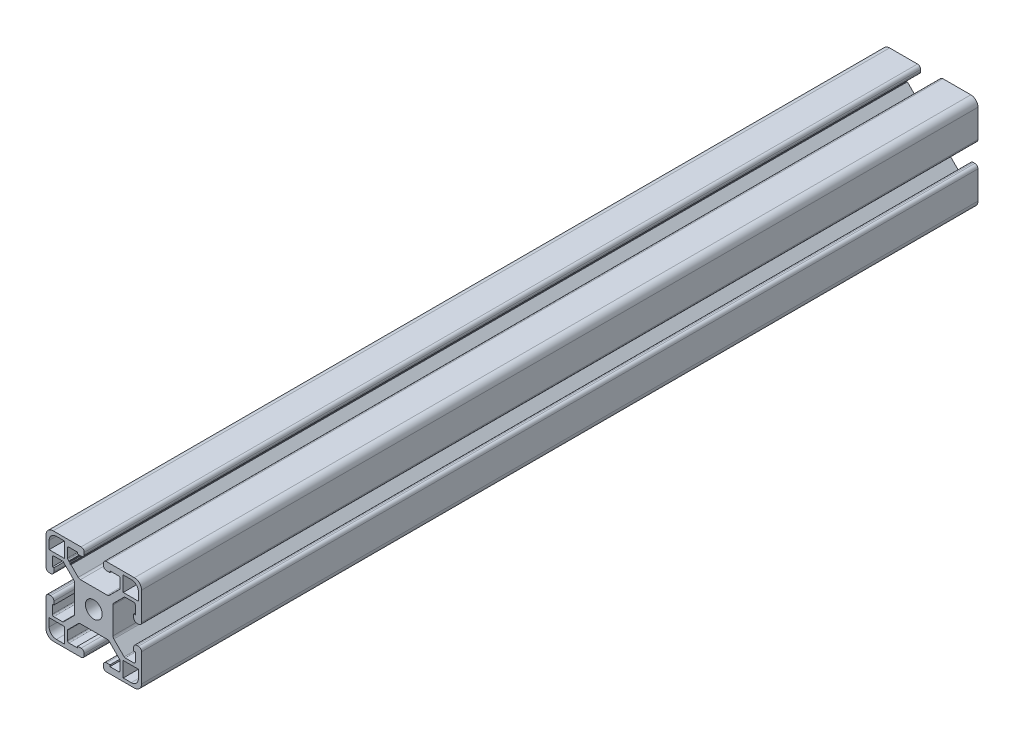
SolidWorks part; units mm, degrees
ref_plane "Front Plane" through (0, 0, 0) normal (0, 0, 1) x (1, 0, 0)
ref_plane "Top Plane" through (0, 0, 0) normal (0, 1, 0) x (1, 0, 0)
ref_plane "Right Plane" through (0, 0, 0) normal (1, 0, 0) x (0, 0, -1)
sketch "Sketch2" plane through (0, 0, 0) normal (0, 0, 1) x (1, 0, 0)
  line L0 (0, 20) -> (0, -20) construction
  line L1 (-20, 0) -> (20, 0) construction
  line L2 (4, -20) -> (20, -20)
  line L3 (20, -20) -> (20, -4)
  line L5 (6.75, -17.36) -> (10.4, -17.36)
  line L7 (0, 0) -> (20, -20) construction
  line L9 (17.36, -6.75) -> (17.36, -10.4)
  line L11 (10.4334, -8.5666) -> (8.5666, -10.4334) construction
  line L12 (11, -16.76) -> (11, -12.8668)
  line L13 (6.1332, -8) -> (11, -12.8668)
  line L14 (16.76, -11) -> (12.8668, -11)
  line L15 (8, -6.1332) -> (12.8668, -11)
  line L16 (4, -20) -> (4, -16.7)
  line L18 (4, -16.7) -> (6.75, -16.7)
  line L19 (6.75, -16.7) -> (6.75, -17.36)
  line L20 (20, -4) -> (16.7, -4)
  line L21 (16.7, -4) -> (16.7, -6.75)
  line L22 (16.7, -6.75) -> (17.36, -6.75)
  line L23 (6.75, -17.36) -> (6.75, -20) construction
  circle A0 centre (0, 0) radius 3.5
  arc A1 (10.4, -17.36) -> (11, -16.76) centre (10.4, -16.76) ccw
  arc A2 (17.36, -10.4) -> (16.76, -11) centre (16.76, -10.4) cw
  point P8 (0, -8)
  point P16 (9.5, -9.5)
  dimension "Center Hole Diameter" = 7
  dimension "D3" = 0.6
  dimension "Rail Height" = 40
  dimension "Rail Width" = 40
  dimension "T-Slot Width" = 8
  dimension "Slot Depth" = 12
  dimension "Inner Slot Width" = 22
  dimension "D1" = 2.75
  dimension "D2" = 3.3
  dimension "D4" = 0.66
sketch "Sketch3" plane through (0, 0, 0) normal (1, 0, 0) x (0, 0, -1)
  line L0 (-175, -20) -> (175, -20) construction
  line L1 (-149.6, 0) -> (149.6, 0) construction
  dimension "Length" = 350
  dimension "D1" = 25.4
sketch "Sketch4" plane through (0, 0, 0) normal (0, 0, 1) x (1, 0, 0)
  line L1 (20, -17) -> (20, -5.32)
  line L2 (20, -4) -> (16.7, -4) construction
  line L3 (16.7, -4) -> (16.7, -6.75) construction
  line L7 (18.02, -4) -> (18.68, -4)
  line L9 (16.7, -5.32) -> (16.7, -6.75)
  line L10 (16.7, -6.75) -> (17.36, -6.75)
  line L11 (17.36, -6.75) -> (17.36, -10.4)
  line L13 (16.76, -11) -> (13.1153, -11)
  line L18 (16.76, -11) -> (12.8668, -11) construction
  line L20 (8, -6.1332) -> (12.8668, -11) construction
  line L22 (4, -20) -> (20, -20) construction
  line L23 (20, -20) -> (20, -4) construction
  line L24 (17, -20) -> (5.32, -20)
  line L25 (4, -18.02) -> (4, -18.68)
  line L26 (4, -20) -> (4, -16.7) construction
  line L27 (4, -16.7) -> (6.75, -16.7) construction
  line L28 (5.32, -16.7) -> (6.75, -16.7)
  line L29 (6.75, -16.7) -> (6.75, -17.36)
  line L30 (6.75, -17.36) -> (10.4, -17.36)
  line L31 (6.1332, -8) -> (11, -12.8668) construction
  line L32 (11, -16.76) -> (11, -12.8668) construction
  line L33 (11, -13.1153) -> (11, -16.76)
  line L34 (0, -8) -> (5.5865, -8)
  line L35 (6.5199, -8.3866) -> (10.8243, -12.691)
  line L36 (12.691, -10.8243) -> (8.3866, -6.5199)
  line L37 (8, 0) -> (8, -5.5865)
  line L38 (-20, 0) -> (20, 0) construction
  line L39 (15.68, -18.68) -> (12.32, -18.68)
  line L40 (12.32, -18.68) -> (12.32, -12.32)
  line L41 (18.68, -12.32) -> (18.68, -15.68)
  line L42 (12.32, -12.32) -> (18.68, -12.32)
  line L43 (0, 0) -> (20, -20) construction
  line L44 (12.32, -18.68) -> (12.32, -20) construction
  line L45 (11, -14.9376) -> (12.32, -14.9376) construction
  line L46 (0, -8) -> (0, -3.5)
  line L47 (8, 0) -> (3.5, 0)
  arc A1 (18.68, -4) -> (20, -5.32) centre (18.68, -5.32) cw
  arc A10 (16.7, -5.32) -> (18.02, -4) centre (18.02, -5.32) cw
  arc A12 (17, -20) -> (20, -17) centre (17, -17) ccw
  arc A13 (4, -18.02) -> (5.32, -16.7) centre (5.32, -18.02) cw
  arc A14 (4, -18.68) -> (5.32, -20) centre (5.32, -18.68) ccw
  arc A15 (10.4, -17.36) -> (11, -16.76) centre (10.4, -16.76) ccw construction
  arc A16 (10.4, -17.36) -> (11, -16.76) centre (10.4, -16.76) ccw
  arc A17 (10.8243, -12.691) -> (11, -13.1153) centre (10.4, -13.1153) cw
  arc A18 (5.5865, -8) -> (6.5199, -8.3866) centre (5.5865, -9.32) cw
  arc A19 (16.76, -11) -> (17.36, -10.4) centre (16.76, -10.4) ccw construction
  arc A20 (16.76, -11) -> (17.36, -10.4) centre (16.76, -10.4) ccw
  arc A21 (12.691, -10.8243) -> (13.1153, -11) centre (13.1153, -10.4) ccw
  arc A22 (8, -5.5865) -> (8.3866, -6.5199) centre (9.32, -5.5865) ccw
  arc A23 (18.68, -15.68) -> (15.68, -18.68) centre (15.68, -15.68) cw
  circle A24 centre (0, 0) radius 3.5 construction
  arc A25 (0, -3.5) -> (3.5, 0) centre (0, 0) ccw
  point P74 (4, -18.35)
  dimension "D2" = 1.32
  dimension "D1" = 1.32
  dimension "D3" = 3
  dimension "D4" = 3
extrude "Boss-Extrude1" add sketch "Sketch4" along normal mid plane 350
mirror "Mirror1" about plane through (0, 0, 0) normal (1, 0, 0) of bodies 134
mirror "Mirror2" about plane through (0, 0, 0) normal (0, 1, 0) of bodies 135
sketch "Sketch5" plane through (0, 0, 0) normal (0, 0, 1) x (1, 0, 0)
  line L1 (-10.4532, 12.32) -> (-10.4532, 11.99)
  line L2 (-6.5199, 8.3866) -> (-10.8243, 12.691) construction
  line L3 (-10.4532, 11.99) -> (-10.1232, 11.99)
  line L4 (-10.1232, 11.99) -> (-9.8899, 11.7567)
  line L5 (-9.8899, 11.7567) -> (-9.8899, 11.4267)
  line L6 (-9.8899, 11.4267) -> (-9.5599, 11.4267)
  line L7 (-10.4532, 12.32) -> (-9.5599, 12.32)
  line L8 (-9.5599, 12.32) -> (-9.5599, 11.4267)
  dimension "D1" = 0.33
extrude "Cut-Extrude1" cut sketch "Sketch5" against normal through all both and the other way through all
equation "\"D3@Sketch2\"=\"T-Slot Width@Sketch2\"*0.075"
equation "\"D1@Boss-Extrude1\"=\"Length@Sketch3\""
equation "\"D1@Sketch2\"=\"Inner Slot Width@Sketch2\"*0.125"
equation "\"D2@Sketch2\"=\"Slot Depth@Sketch2\"*0.275"
equation "\"D4@Sketch2\"=\"D2@Sketch2\"*0.2"
equation "\"D1@Sketch4\"=\"D2@Sketch2\"*0.4"
equation "\"D2@Sketch4\"=\"D1@Sketch4\""
equation "\"D3@Sketch4\"=\"Rail Height@Sketch2\"*0.075"
equation "\"D4@Sketch4\"=\"Rail Height@Sketch2\"*0.075"
equation "\"D1@Sketch5\"=\"D4@Sketch2\"*0.5"
